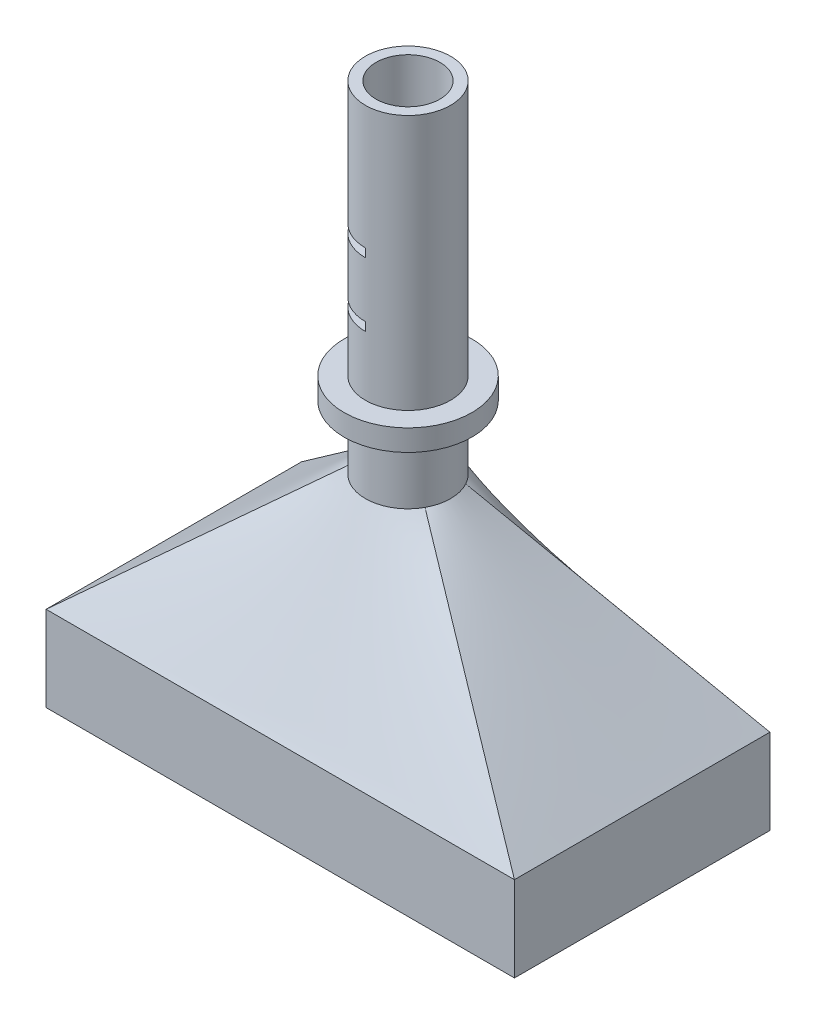
SolidWorks part; units mm, degrees
ref_plane "Front Plane" through (0, 0, 0) normal (0, 0, 1) x (1, 0, 0)
ref_plane "Top Plane" through (0, 0, 0) normal (0, 1, 0) x (1, 0, 0)
ref_plane "Right Plane" through (0, 0, 0) normal (1, 0, 0) x (0, 0, -1)
sketch "Sketch1" plane through (0, 0, 0) normal (0, 1, 0) x (1, 0, 0)
  line L1 (-55, -30) -> (55, -30)
  line L2 (-55, -30) -> (-55, 30)
  line L3 (-55, 30) -> (55, 30)
  line L4 (55, -30) -> (55, 30)
  line L5 (-55, -30) -> (55, 30) construction
  line L6 (-55, 30) -> (55, -30) construction
  point P0 (0, 0)
  dimension "D1" = 60
  dimension "D2" = 110
ref_plane "Plane1" through (0, 60, 0) normal (0, 1, 0) x (1, 0, 0)
sketch "Sketch2" plane through (0, 60, 0) normal (0, 1, 0) x (1, 0, 0)
  circle A0 centre (0, 0) radius 10
  dimension "D1" = 20
ref_plane "Plane2" through (0, 20, 0) normal (0, 1, 0) x (1, 0, 0)
sketch "Sketch4" plane through (0, 20, 0) normal (0, 1, 0) x (1, 0, 0)
  line L1 (-55, 30) -> (55, 30)
  line L2 (-55, 30) -> (-55, -30)
  line L3 (-55, -30) -> (55, -30)
  line L4 (55, 30) -> (55, -30)
  line L5 (-55, 30) -> (55, -30) construction
  line L6 (-55, -30) -> (55, 30) construction
  point P0 (0, 0)
  dimension "D1" = 60
  dimension "D2" = 110
extrude "Boss-Extrude3" add sketch "Sketch1" along normal blind 20 contours L1 L4 L3 L2
loft "Loft5" add profiles "Sketch4", "Sketch2"
sketch "Sketch7" plane through (0, 0, 0) normal (0, -1, 0) x (1, 0, 0)
  line L1 (50, -25) -> (-50, -25)
  line L2 (50, -25) -> (50, 25)
  line L3 (50, 25) -> (-50, 25)
  line L4 (-50, -25) -> (-50, 25)
  line L5 (50, -25) -> (-50, 25) construction
  line L6 (50, 25) -> (-50, -25) construction
  point P0 (0, 0)
  dimension "D1" = 50
  dimension "D2" = 100
extrude "Cut-Extrude3" cut sketch "Sketch7" against normal blind 20
sketch "Sketch8" plane through (0, 20, 0) normal (0, -1, 0) x (1, 0, 0)
  circle A0 centre (0, 0) radius 7.5
  dimension "D1" = 15
extrude "Cut-Extrude5" cut sketch "Sketch8" against normal blind 40
sketch "Sketch10" plane through (0, 20, 0) normal (0, -1, 0) x (1, 0, 0)
  line L1 (50, -25) -> (-50, -25)
  line L2 (50, -25) -> (50, 25)
  line L3 (50, 25) -> (-50, 25)
  line L4 (-50, -25) -> (-50, 25)
  line L5 (50, -25) -> (-50, 25) construction
  line L6 (50, 25) -> (-50, -25) construction
  point P0 (0, 0)
sketch "Sketch11" plane through (0, 60, 0) normal (0, 1, 0) x (1, 0, 0)
  circle A0 centre (0, 0) radius 7.5
loft "Cut-Loft1" cut profiles "Sketch11", "Sketch10"
sketch "Sketch12" plane through (0, 60, 0) normal (0, 1, 0) x (1, 0, 0)
  circle A0 centre (0, 0) radius 10
  circle A1 centre (0, 0) radius 7.5
  dimension "D1" = 15
  dimension "D2" = 20
extrude "Boss-Extrude4" add sketch "Sketch12" along normal blind 80
ref_plane "Plane3" through (0, 80, 0) normal (0, 1, 0) x (1, 0, 0)
sketch "Sketch14" plane through (0, 80, 0) normal (0, 1, 0) x (1, 0, 0)
  circle A0 centre (0, 0) radius 10
  circle A1 centre (0, 0) radius 15
extrude "Boss-Extrude5" add sketch "Sketch14" against normal blind 5
ref_plane "Plane7" through (-8.54, 0, 0) normal (-1, 0, 0) x (0, 0, 1)
sketch "Sketch19" plane through (-8.54, 0, 0) normal (-1, 0, 0) x (0, 0, 1)
  line L0 (0, 80) -> (0, 100) construction
  line L1 (10, 80) -> (-10, 80) construction
  circle A0 centre (0, 100) radius 1
  dimension "D1" = 20
extrude "Cut-Extrude9" cut sketch "Sketch19" against normal blind 5
sketch "Sketch21" plane through (0, 0, 0) normal (1, 0, 0) x (0, 0, -1)
  line L0 (0, 80) -> (0, 95) construction
  line L1 (15, 80) -> (-15, 80) construction
  line L2 (0, 95) -> (0, 110) construction
  line L3 (0, 110) -> (0, 111)
  line L4 (0, 111) -> (10, 111)
  line L5 (10, 80) -> (10, 140) construction
  line L6 (10, 111) -> (10, 109)
  line L7 (10, 109) -> (-10, 109)
  line L8 (-10, 109) -> (-10, 111)
  line L9 (0, 111) -> (-10, 111)
  line L15 (0, 95) -> (0, 94)
  line L16 (0, 94) -> (-10, 94)
  line L17 (-10, 140) -> (-10, 80) construction
  line L18 (-10, 94) -> (-10, 96)
  line L19 (-10, 140) -> (-10, 80) construction
  line L20 (-10, 96) -> (10, 96)
  line L21 (10, 80) -> (10, 140) construction
  line L22 (10, 96) -> (10, 94)
  line L23 (10, 80) -> (10, 140) construction
  line L24 (10, 94) -> (0, 94)
  dimension "D1" = 15
  dimension "D2" = 15
  dimension "D3" = 1
  dimension "D4" = 2
  dimension "D5" = 2
  dimension "D6" = 10
  dimension "D7" = 1
  dimension "D8" = 2
extrude "Cut-Extrude10" cut sketch "Sketch21" against normal blind 11 contours L16 L18 L20 L22 L24 | L4 L6 L7 L8 L9
